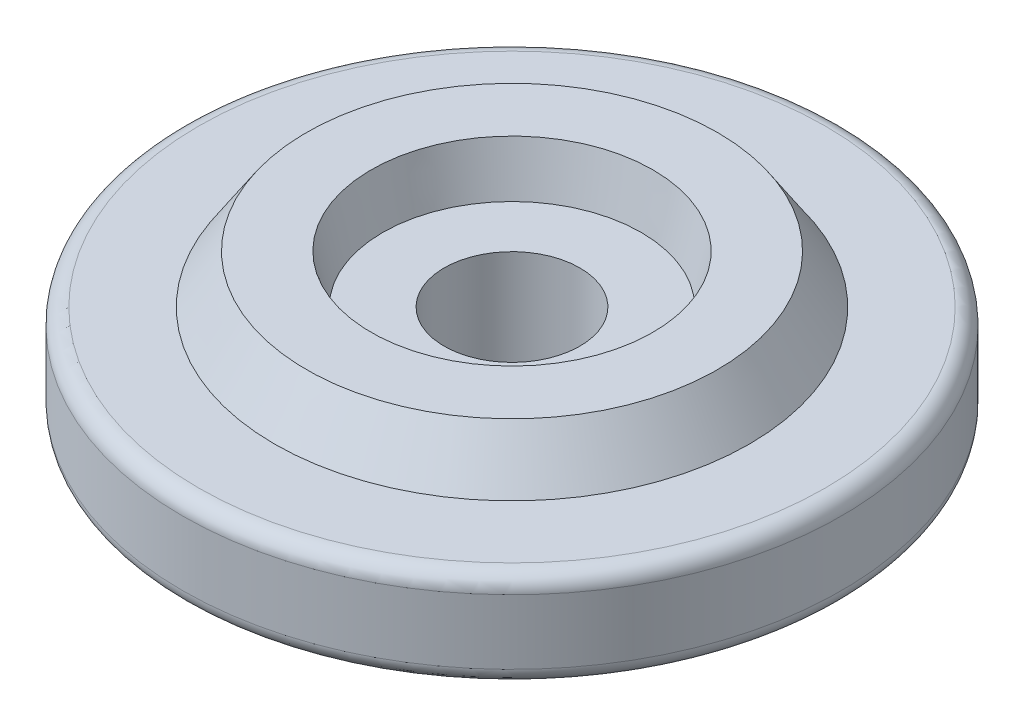
SolidWorks part; units mm, degrees
ref_plane "Front Plane" through (0, 0, 0) normal (0, 0, 1) x (1, 0, 0)
ref_plane "Top Plane" through (0, 0, 0) normal (0, 1, 0) x (1, 0, 0)
ref_plane "Right Plane" through (0, 0, 0) normal (1, 0, 0) x (0, 0, -1)
sketch "Sketch1" plane through (0, 0, 0) normal (0, 0, 1) x (1, 0, 0)
  line L0 (2.1, 0) -> (2.1, 3)
  line L1 (2.1, 3) -> (4, 3)
  line L2 (4, 3) -> (4.3594, 4.5)
  line L3 (4.3594, 4.5) -> (6.3594, 4.5)
  line L4 (6.3594, 4.5) -> (7.348, 3)
  line L5 (7.348, 3) -> (9.7, 3)
  line L6 (10.2, 2.5) -> (10.2, 0.5)
  line L7 (9.7, 0) -> (2.1, 0)
  line L8 (0, 0) -> (0, 4.2807) construction
  arc A0 (10.2, 0.5) -> (9.7, 0) centre (9.7, 0.5) cw
  arc A1 (9.7, 3) -> (10.2, 2.5) centre (9.7, 2.5) cw
  point P11 (3.5368, 2.8744)
  point P12 (0, 0)
  point P13 (0, 0)
  point P14 (7.1561, 3.8889)
  point P15 (4.3594, 4)
  point P16 (7.348, 3)
  point P19 (10.2, 0)
  point P22 (10.2, 3)
  dimension "D7" = 0.5
  dimension "D1" = 10.2
  dimension "D2" = 2.1
  dimension "D3" = 4
  dimension "D4" = 3
  dimension "D5" = 4.5
  dimension "D6" = 2
revolve "Revolve1" add sketch "Sketch1" angle 360 about L8
